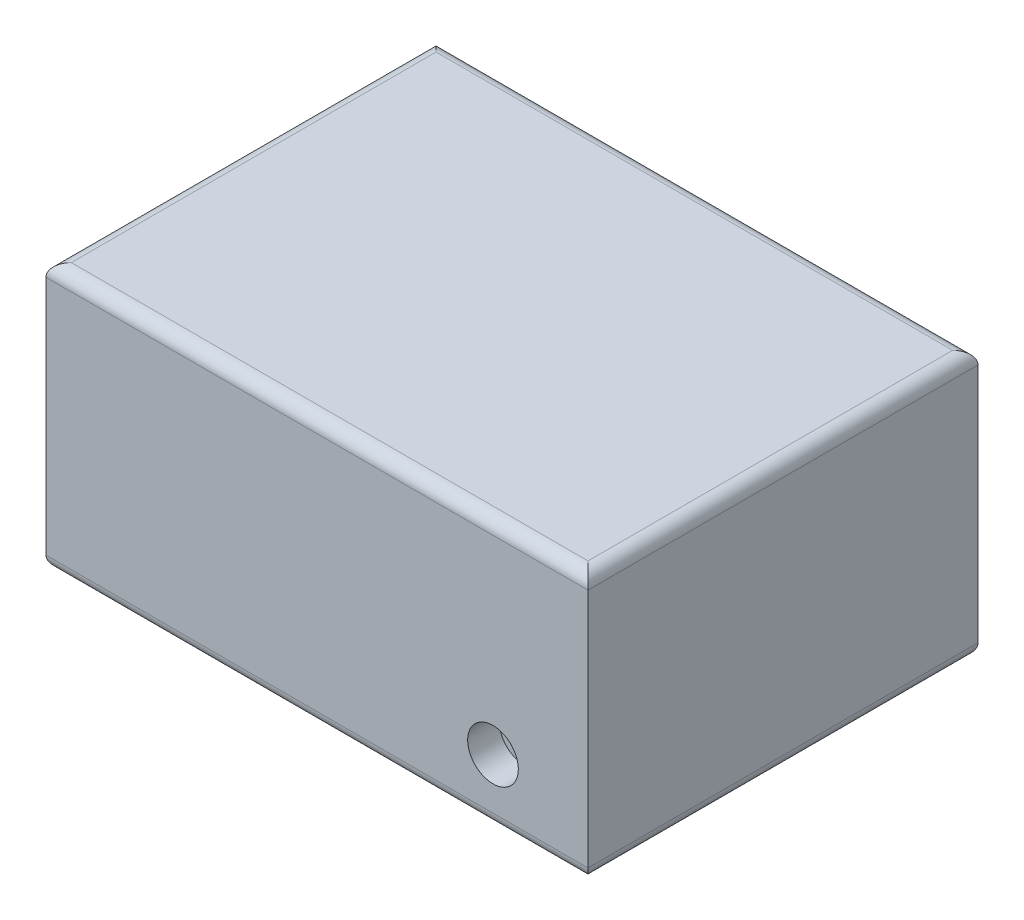
SolidWorks part; units mm, degrees
material "AISI 304"
ref_plane "前视基准面" through (0, 0, 0) normal (0, 0, 1) x (1, 0, 0)
ref_plane "上视基准面" through (0, 0, 0) normal (0, 1, 0) x (1, 0, 0)
ref_plane "右视基准面" through (0, 0, 0) normal (1, 0, 0) x (0, 0, -1)
other "Configuration Table"
sketch "草图1" plane through (0, 0, 0) normal (0, 1, 0) x (1, 0, 0)
  line L1 (-42.8, -30.8) -> (42.8, -30.8)
  line L2 (-42.8, -30.8) -> (-42.8, 30.8)
  line L3 (-42.8, 30.8) -> (42.8, 30.8)
  line L4 (42.8, -30.8) -> (42.8, 30.8)
  line L5 (-42.8, -30.8) -> (42.8, 30.8) construction
  line L6 (-42.8, 30.8) -> (42.8, -30.8) construction
  point P0 (0, 0)
  dimension "D1" = 85.6
  dimension "D2" = 61.6
extrude "凸台-拉伸1" add sketch "草图1" along normal blind 42
sketch "草图2" plane through (0, 0, 30.8) normal (0, 0, 1) x (1, 0, 0)
  line L0 (42.8, 42) -> (42.8, 0) construction
  line L1 (-42.8, 0) -> (42.8, 0) construction
  circle A0 centre (27.8, 10) radius 4
  dimension "D1" = 8
  dimension "D2" = 15
  dimension "D3" = 10
extrude "切除-拉伸1" cut sketch "草图2" against normal blind 5
fillet "圆角1" radius 2 8 edges at (0, 0, -30.8) (-42.8, 0, 0) (0, 0, 30.8) (42.8, 0, 0) (0, 42, 30.8) (-42.8, 42, 0) (0, 42, -30.8) (42.8, 42, 0)
